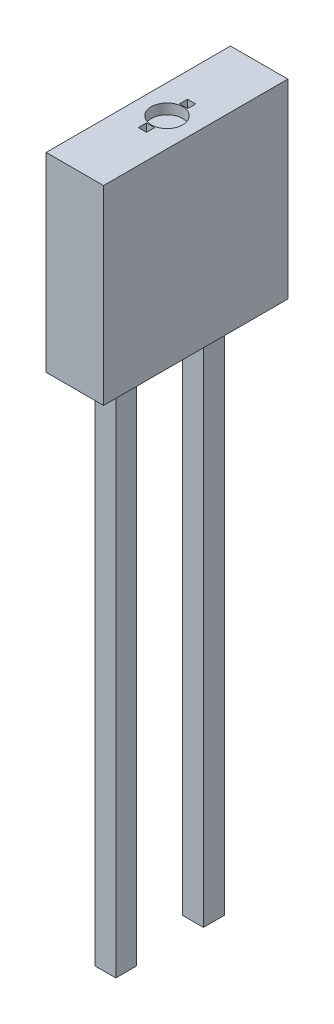
SolidWorks part; units mm, degrees
ref_plane "Alzado" through (0, 0, 0) normal (0, 0, 1) x (1, 0, 0)
ref_plane "Planta" through (0, 0, 0) normal (0, 1, 0) x (1, 0, 0)
ref_plane "Vista lateral" through (0, 0, 0) normal (1, 0, 0) x (0, 0, -1)
sketch "Croquis1" plane through (0, 0, 0) normal (0, 1, 0) x (1, 0, 0)
  line L1 (-1.4, 0) -> (0, 0)
  line L2 (-1.4, 0) -> (-1.4, -4.5)
  line L3 (-1.4, -4.5) -> (0, -4.5)
  line L4 (0, 0) -> (0, -4.5)
  dimension "D1" = 4.5
  dimension "D2" = 1.4
extrude "Saliente-Extruir1" add sketch "Croquis1" along normal blind 4.65
sketch "Croquis3" plane through (0, 4.65, 0) normal (0, 1, 0) x (1, 0, 0)
  line L0 (-0.7, -4.5) -> (-0.7, 0) construction
  line L1 (-1.4, -4.5) -> (0, -4.5) construction
  line L2 (0, 0) -> (-1.4, 0) construction
  circle A0 centre (-0.7, -2.25) radius 0.3835
  dimension "D1" = 0.7669
extrude "Cortar-Extruir1" cut sketch "Croquis3" against normal blind 0.25
sketch "Croquis4" plane through (0, 4.65, 0) normal (0, 1, 0) x (1, 0, 0)
  line L0 (-0.7, -1.8665) -> (-0.7, -1.75) construction
  line L1 (-0.7, -2.6335) -> (-0.7, -2.75) construction
  line L2 (-0.8, -1.65) -> (-0.8, -1.85)
  line L3 (-0.8, -1.65) -> (-0.6, -1.65)
  line L4 (-0.8, -1.85) -> (-0.6, -1.85)
  line L5 (-0.6, -1.65) -> (-0.6, -1.85)
  line L6 (-0.8, -1.65) -> (-0.6, -1.85) construction
  line L7 (-0.8, -1.85) -> (-0.6, -1.65) construction
  line L8 (-0.8, -2.85) -> (-0.8, -2.65)
  line L9 (-0.8, -2.85) -> (-0.6, -2.85)
  line L10 (-0.8, -2.65) -> (-0.6, -2.65)
  line L11 (-0.6, -2.85) -> (-0.6, -2.65)
  line L12 (-0.8, -2.85) -> (-0.6, -2.65) construction
  line L13 (-0.8, -2.65) -> (-0.6, -2.85) construction
  line L14 (-1.0835, -2.25) -> (-0.3165, -2.25) construction
  circle A0 centre (-0.7, -2.25) radius 0.3835 construction
  circle A1 centre (-0.7, -2.25) radius 0.3835 construction
  dimension "D1" = 0.2
  dimension "D2" = 0.8
extrude "Cortar-Extruir5" cut sketch "Croquis4" against normal blind 0.25
sketch "Croquis5" plane through (0, 0, 0) normal (0, -1, 0) x (1, 0, 0)
  line L0 (-1.4, 4.5) -> (0, 4.5) construction
  line L1 (0, 4.5) -> (0, 0) construction
  line L5 (-0.445, 3.755) -> (-0.955, 3.755)
  line L6 (-0.445, 3.755) -> (-0.445, 3.245)
  line L7 (-0.445, 3.245) -> (-0.955, 3.245)
  line L8 (-0.955, 3.755) -> (-0.955, 3.245)
  line L9 (-0.445, 3.755) -> (-0.955, 3.245) construction
  line L10 (-0.445, 3.245) -> (-0.955, 3.755) construction
  line L11 (-0.445, 1.1063) -> (-0.955, 1.1063)
  line L12 (-0.445, 1.1063) -> (-0.445, 1.6163)
  line L13 (-0.445, 1.6163) -> (-0.955, 1.6163)
  line L14 (-0.955, 1.1063) -> (-0.955, 1.6163)
  line L15 (-0.445, 1.1063) -> (-0.955, 1.6163) construction
  line L16 (-0.445, 1.6163) -> (-0.955, 1.1063) construction
  point P0 (-0.7, 4.5)
  dimension "D1" = 0.745
  dimension "D2" = 1.6287
  dimension "D3" = 0.445
  dimension "D4" = 0.51
extrude "Saliente-Extruir2" add sketch "Croquis5" along normal blind 12.7
